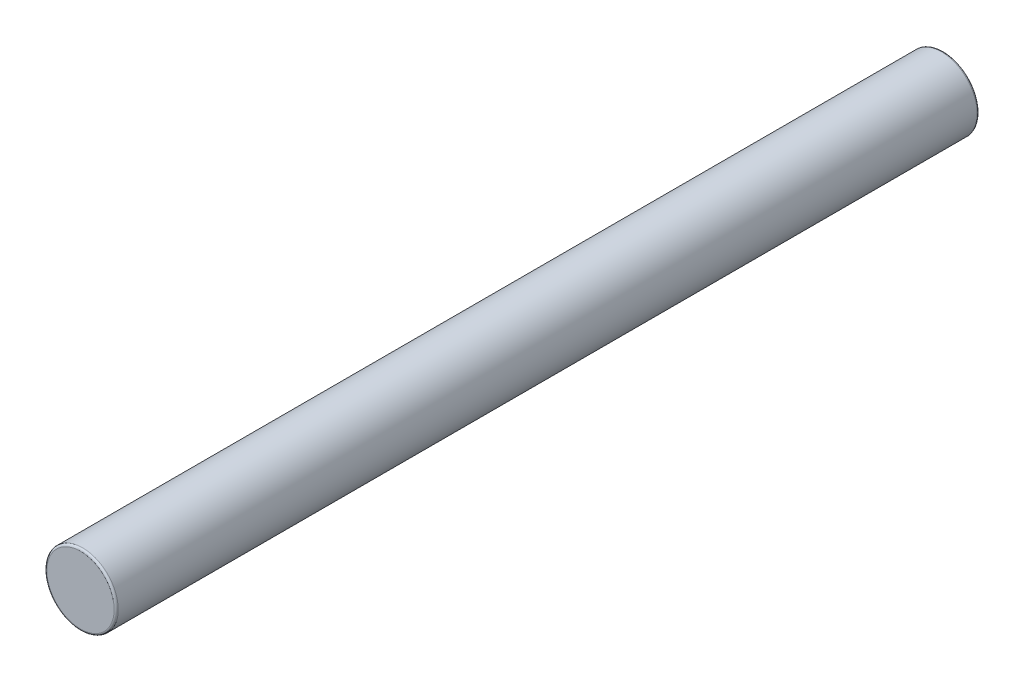
SolidWorks part; units mm, degrees
material "AISI 316 Stainless Steel Sheet (SS)"
ref_plane "Front Plane" through (0, 0, 0) normal (0, 0, 1) x (1, 0, 0)
ref_plane "Top Plane" through (0, 0, 0) normal (0, 1, 0) x (1, 0, 0)
ref_plane "Right Plane" through (0, 0, 0) normal (1, 0, 0) x (0, 0, -1)
sketch "Sketch1" plane through (0, 0, 0) normal (0, 0, 1) x (1, 0, 0)
  circle A0 centre (0, 0) radius 3.475
  dimension "D1" = 6.95
extrude "Boss-Extrude1" add sketch "Sketch1" along normal mid plane 84
fillet "Fillet1" radius 0.2 2 edges at (3.475, 0, 42) (3.475, 0, -42)
